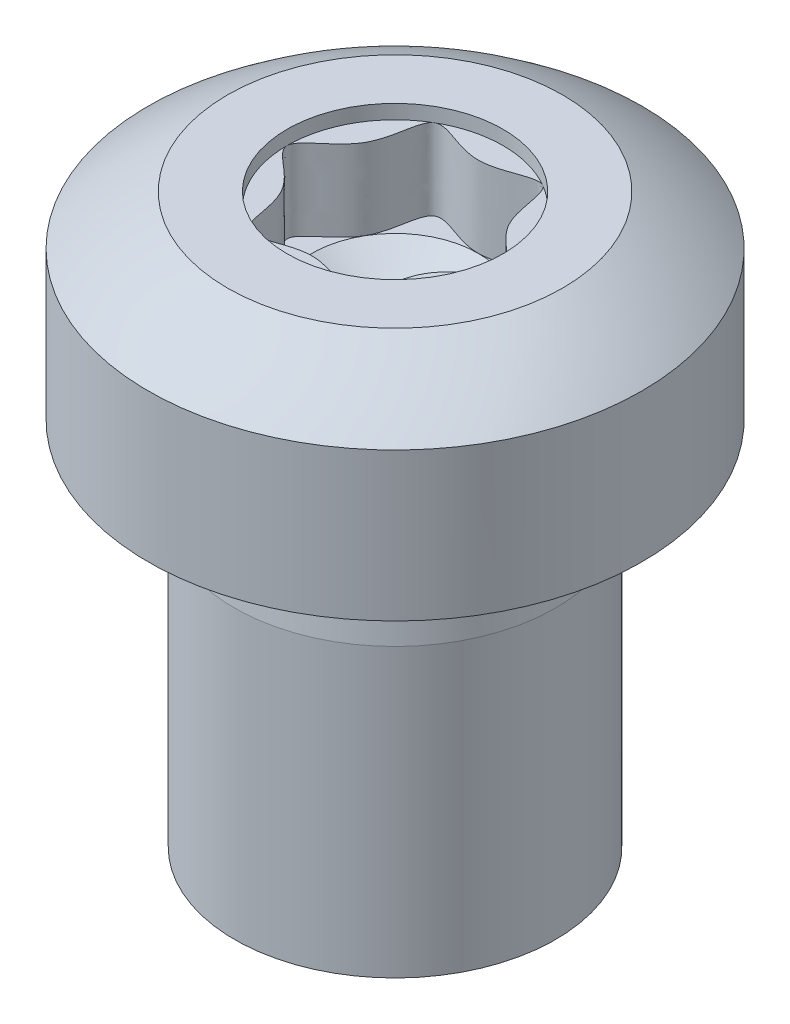
SolidWorks part; units mm, degrees
ref_plane "Front" through (0, 0, 0) normal (0, 0, 1) x (1, 0, 0)
ref_plane "Top" through (0, 0, 0) normal (0, 1, 0) x (1, 0, 0)
ref_plane "Right" through (0, 0, 0) normal (1, 0, 0) x (0, 0, -1)
sketch "Sketch1" plane through (0, 0, 0) normal (0, 0, 1) x (1, 0, 0)
  line L0 (0, 0) -> (0, 34.6184) construction
  line L1 (0, 0) -> (1.3, 0)
  line L2 (1.3, 0) -> (1.3, 3)
  line L3 (1.3, 3) -> (2, 3)
  line L4 (2, 3) -> (2, 4.6)
  line L5 (2, 4.6) -> (0, 4.6)
  line L6 (0, 4.6) -> (0, 0)
  line L7 (2, 3) -> (2.4, 3) construction
  line L8 (2.4, 3) -> (2.4, 0.8) construction
  dimension "HEAD_DIA" = 4
  dimension "HEAD_HT" = 1.6
  dimension "LENGTH" = 3
  dimension "DIA" = 2.6
  dimension "pitch" = 0.4
  dimension "thread_length" = 2.2
revolve "BODY" add sketch "Sketch1" angle 360 about L0
cosmetic thread "ThreadCosmetic" [suppressed]
sketch "Sketch2" plane through (0, 0, 0) normal (0, 0, 1) x (1, 0, 0)
  line L0 (2, 4.2) -> (0, 1.702) construction
  line L3 (2, 3) -> (2, 4.6) construction
  line L4 (0, 0) -> (0, 34.6184) construction
  line L5 (0, 4.902) -> (0, 5.3842)
  line L6 (3.2, 1.702) -> (3.2, 5.3842)
  line L7 (3.2, 5.3842) -> (0, 5.3842)
  line L8 (0, 5.3842) -> (3.2, 5.3842)
  arc A0 (3.2, 1.702) -> (0, 4.902) centre (0, 1.702) ccw
  dimension "SPHERE_DIA" = 3.2
  dimension "D1" = 0.4
  dimension "D2" = 0.4822
revolve "HEAD-CUT" cut sketch "Sketch2" angle 360 about axis through (0, 0, 0) along (0, 1, 0)
sketch "Sketch4" plane through (0, 0, 0) normal (0, 0, 1) x (1, 0, 0)
  line L0 (-1.3, 2.3264) -> (-1.2436, 2.9)
  line L1 (-1.3, 3) -> (-1.3, 0) construction
  line L2 (-1.3, 3) -> (-1.3, 2.3264)
  arc A0 (-1.2436, 2.9) -> (-1.3, 3) centre (-1.3431, 2.9098) ccw
  dimension "CONER_RAD" = 0.1
  dimension "D1" = 0.1
  dimension "GAP" = 0.6736
revolve "GAP" cut sketch "Sketch4" angle 360 about axis through (0, 0, 0) along (0, 1, 0)
sketch "Sketch5" plane through (0, 4.6, 0) normal (0, 1, 0) x (-1, 0, 0)
  line L0 (0, 0.6731) -> (0, 0) construction
  line L1 (0, 0) -> (0.4375, 0.7578) construction
  circle A0 centre (0, 0) radius 0.6731 construction
  circle A1 centre (0, 0) radius 0.875
  spline S0 degree 3 poles (0, 0.5431) (0.5387, 0.933) (0.4704, 0.2716) (1.0773, 0) (0.4704, -0.2716) (0.5387, -0.933) (0, -0.5431) (-0.5387, -0.933) (-0.4704, -0.2716) (-1.0773, 0) (-0.4704, 0.2716) (-0.5387, 0.933) (0, 0.5431) (0.5387, 0.933) (0.4704, 0.2716) knots -0.25 -0.166667 -0.083333 0 0.083333 0.166667 0.25 0.333333 0.416667 0.5 0.583333 0.666667 0.75 0.833333 0.916667 1 1.083333 1.166667 1.25 only from (0.4375, 0.7578) to (0.4375, 0.7578)
  point P4 (0, 0.6731)
  point P5 (0.4375, 0.7578)
  point P9 (0.875, 0)
  point P10 (0.5829, 0.3365)
  point P11 (0.5829, -0.3365)
  point P12 (0, -0.6731)
  point P13 (-0.5829, -0.3365)
  point P14 (-0.5829, 0.3365)
  point P15 (0.4375, -0.7578)
  point P16 (-0.4375, -0.7578)
  point P19 (-0.875, 0)
  point P20 (-0.4375, 0.7578)
  dimension "slot_dia" = 1.75
  dimension "D3" = 1.3462
  dimension "D1" = 30
extrude "Recess-Cut-Extrude1" cut sketch "Sketch5" against normal blind 0.77
sketch "Sketch3" plane through (0, 0, 0) normal (0, 0, 1) x (1, 0, 0)
  line L0 (0, 3.4414) -> (0.6731, 3.83)
  line L1 (0, 0) -> (0, 34.6184) construction
  line L2 (0.6731, 3.83) -> (0, 3.83)
  line L3 (0, 3.83) -> (0, 3.4414)
  dimension "D1" = 60
  dimension "DRILL_RAD" = 0.6731
  dimension "SLOT_DEP" = 0.77
revolve "DRILL-CUT" cut sketch "Sketch3" angle 360 about axis through (0, 0, 0) along (0, 1, 0)
sketch "Sketch6" plane through (0, 0, 0) normal (0, 0, 1) x (1, 0, 0)
  line L0 (1.3, 0) -> (1.0835, 0.125)
  line L1 (1.0835, 0.125) -> (1.3, 0.25)
  line L4 (1.3, 0.25) -> (1.3, 0)
  line L5 (0, 0) -> (0, 34.6184) construction
  dimension "D1" = 1.0835
revolve "ThreadSchematic" [suppressed] cut sketch "Sketch6" angle 360 about axis through (0, 0, 0) along (0, 1, 0)
pattern_linear "ThdSchPat" [suppressed] count 6 spacing 0.4 along (0, 1, 0)
sketch "Sketch7" plane through (0, 4.6, 0) normal (0, 1, 0) x (-1, 0, 0)
  circle A0 centre (0, 0) radius 0.875
  dimension "D1" = 1.75
extrude "Recess-Cut-Extrude2" cut sketch "Sketch7" against normal blind 0.1155
equation "\"D1@Sketch2\" = \"HEAD_HT@Sketch1\" * 0.25"
equation "\"D1@Sketch4\" = \"CONER_RAD@Sketch4\""
equation "\"D1@Recess-Cut-Extrude1\" = \"SLOT_DEP@Sketch3\""
equation "\"D1@Sketch7\" = \"slot_dia@Sketch5\""
equation "\"D1@Recess-Cut-Extrude2\" = \"SLOT_DEP@Sketch3\" * 0.15"
equation "\"D3@Sketch5\" = \"slot_dia@Sketch5\" / 1.3"
equation "\"DRILL_RAD@Sketch3\" = \"D3@Sketch5\" * 0.5"
equation "\"D1@ThreadCosmetic\" = \"thread_length@Sketch1\""
equation "\"D2@ThreadCosmetic\" = \"DIA@Sketch1\" - 1.0825 * \"pitch@Sketch1\""
equation "\"D1@Sketch6\" = \"D2@ThreadCosmetic\" / 2"
equation "\"D3@ThdSchPat\" = \"pitch@Sketch1\""
equation "\"D1@ThdSchPat\" = \"thread_length@Sketch1\" / \"pitch@Sketch1\""
